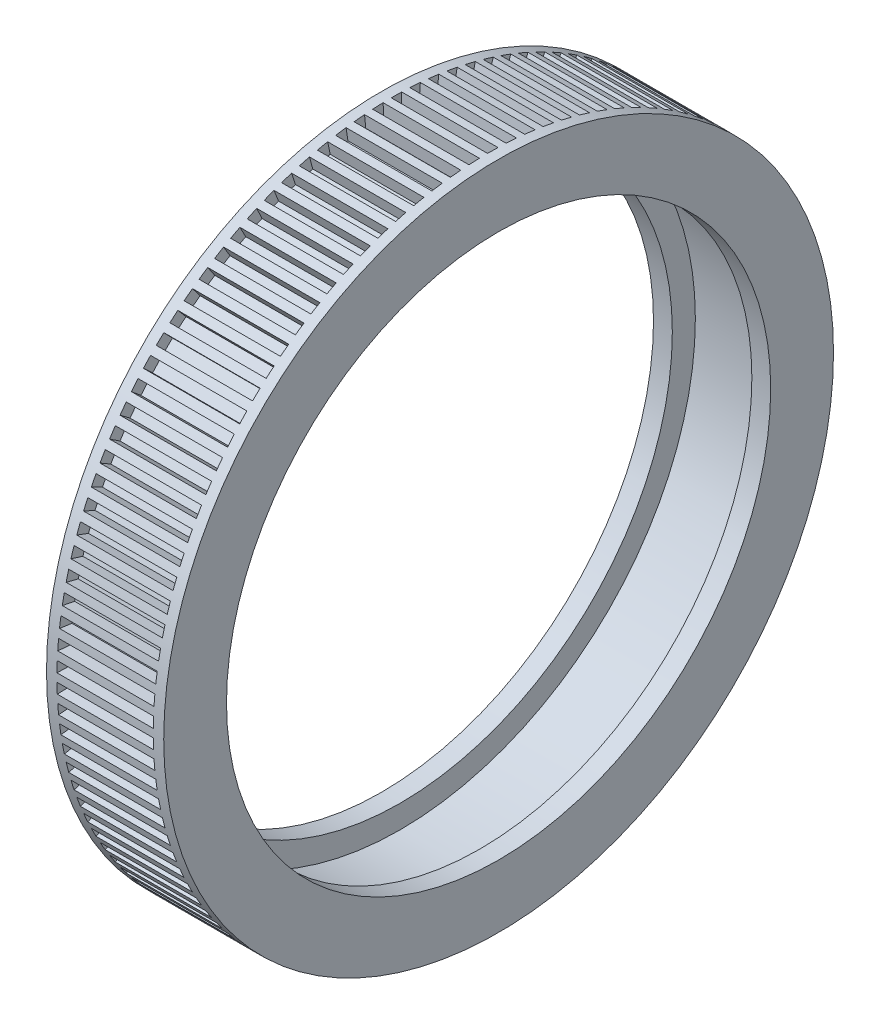
SolidWorks part; units mm, degrees
ref_plane "Přední rovina" through (0, 0, 0) normal (0, 0, 1) x (1, 0, 0)
ref_plane "Horní rovina" through (0, 0, 0) normal (0, 1, 0) x (1, 0, 0)
ref_plane "Pravá rovina" through (0, 0, 0) normal (1, 0, 0) x (0, 0, -1)
sketch "Skica1" plane through (0, 0, 0) normal (0, 0, 1) x (1, 0, 0)
  line L0 (0, 16) -> (0, 0) construction
  line L1 (2.8, 16) -> (-2.8, 16)
  line L2 (-2.8, 16) -> (-2.8, 13)
  line L3 (-2.8, 13) -> (-1.9, 13)
  line L4 (-1.9, 13) -> (-1.9, 14.1)
  line L5 (-1.9, 14.1) -> (1.9, 14.1)
  line L6 (1.9, 13) -> (1.9, 14.1)
  line L7 (2.8, 13) -> (1.9, 13)
  line L8 (2.8, 16) -> (2.8, 13)
  line L9 (-7.5774, 0) -> (6.8729, 0) construction
  point P9 (0, 14.1)
  dimension "D1" = 16
  dimension "D2" = 5.6
  dimension "D3" = 0.9
  dimension "D4" = 3.8
  dimension "D5" = 3
  dimension "D6" = 1.1
revolve "Rotovat1" add sketch "Skica1" angle 360 about L9
sketch "Skica2" plane through (0, 0, 0) normal (0, 0, 1) x (1, 0, 0)
  line L0 (0, 16) -> (0, -16) construction
  line L1 (2.8, 16) -> (-2.8, 16) construction
  line L2 (-2.8, -16) -> (2.8, -16) construction
  line L4 (-2.3, 0.25) -> (2.3, 0.25)
  line L5 (-2.3, 0.25) -> (-2.3, -0.25)
  line L6 (-2.3, -0.25) -> (2.3, -0.25)
  line L7 (2.3, 0.25) -> (2.3, -0.25)
  line L9 (2.3, 0) -> (-2.3, 0) construction
  point P12 (0, 0)
  dimension "D1" = 4.6
  dimension "D2" = 0.5
extrude "Odebrat vysunutím1" cut sketch "Skica2" against normal blind 0.7 from offset 15.4 offset against normal yes
pattern_circular "Kruhové pole1" count 113 over 360 about axis through (0, 0, 0) along (1, 0, 0) of "Odebrat vysunutím1"
